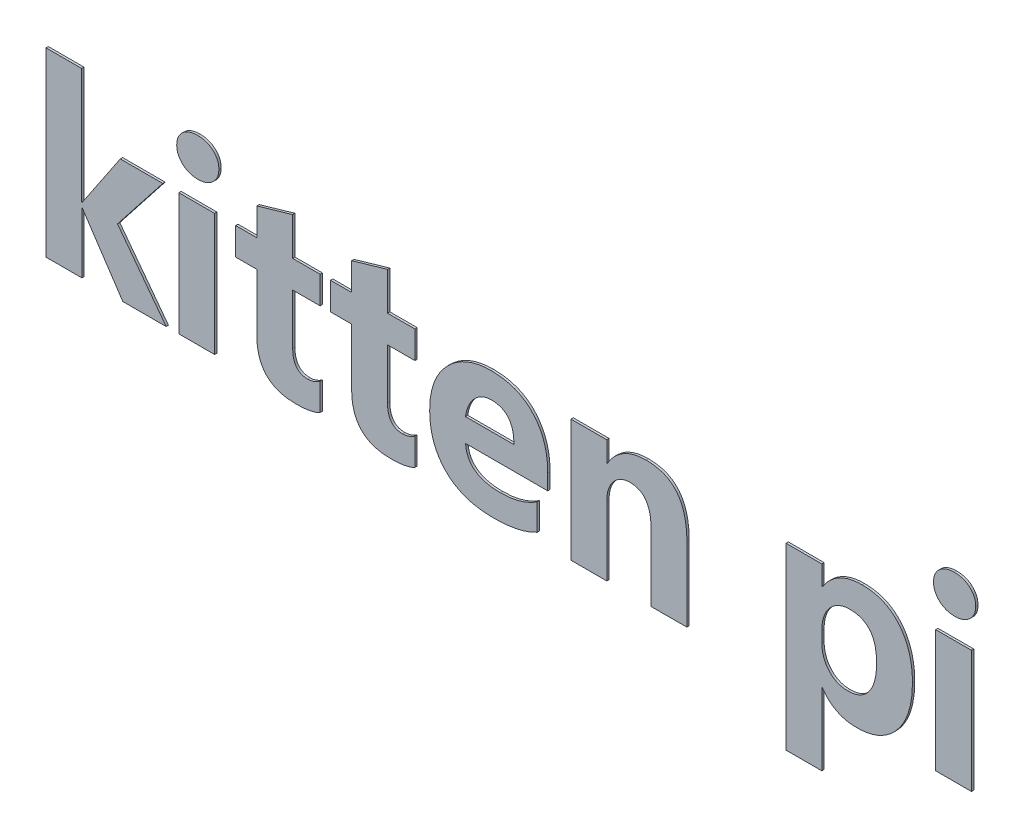
SolidWorks part; units mm, degrees
ref_plane "前视基准面" through (0, 0, 0) normal (0, 0, 1) x (1, 0, 0)
ref_plane "上视基准面" through (0, 0, 0) normal (0, 1, 0) x (1, 0, 0)
ref_plane "右视基准面" through (0, 0, 0) normal (1, 0, 0) x (0, 0, -1)
other "Configuration Table"
sketch "草图1" plane through (0, 0, 138.8176) normal (0, 0, 1) x (1, 0, 0)
  line L0 (-71.2721, 42.2354) -> (-71.2721, -38.3394) construction
  line L1 (-71.2721, 42.2354) -> (-71.2721, -38.3394) construction
  line L3 (-49.0573, 42.2354) -> (-71.2721, 42.2354) construction
  line L4 (-71.2721, -38.3394) -> (53.8279, -38.3394) construction
  line L5 (-71.2721, -10.3394) -> (53.8279, -10.3394) construction
  line L6 (53.8279, -25.6148) -> (53.8279, 19.2529) construction
  text T0 "kitten pi" font "微软雅黑" height 15
  dimension "D1" = 0
  dimension "D2" = 28
extrude "凸台-拉伸1" add sketch "草图1" against normal blind 0.2
